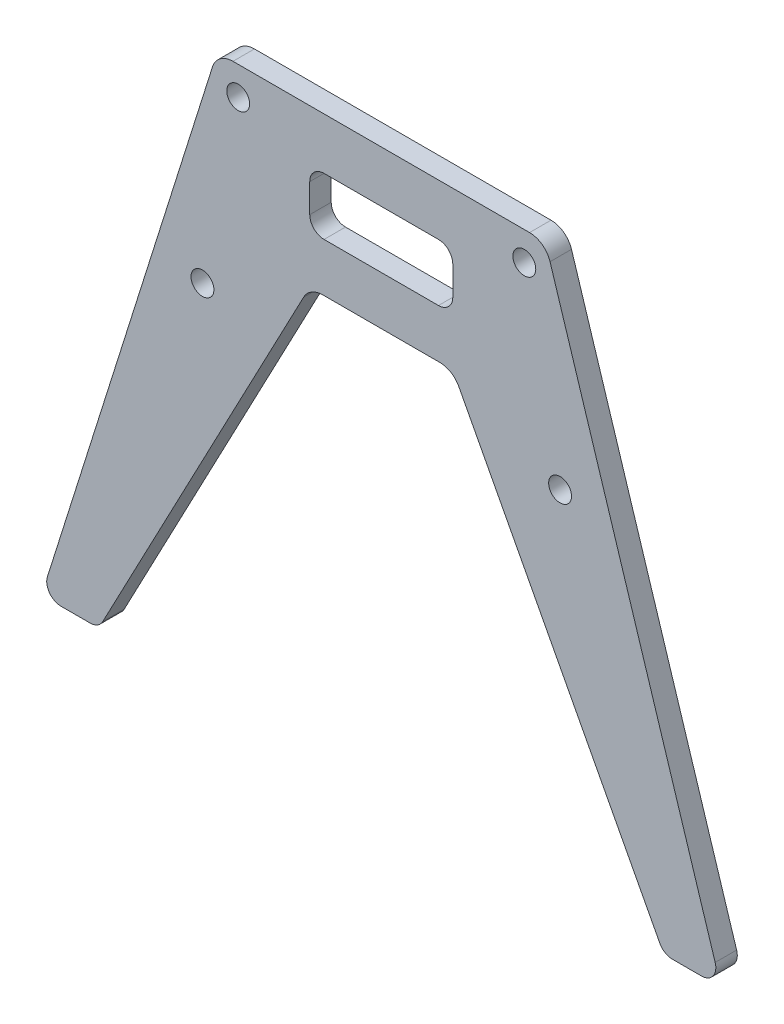
SolidWorks part; units mm, degrees
material "Thornel Mat VMA"
ref_plane "前视基准面" through (0, 0, 0) normal (0, 0, 1) x (1, 0, 0)
ref_plane "上视基准面" through (0, 0, 0) normal (0, 1, 0) x (1, 0, 0)
ref_plane "右视基准面" through (0, 0, 0) normal (1, 0, 0) x (0, 0, -1)
other "Configuration Table"
sketch "草图2" plane through (0, 0, 0) normal (0, 0, 1) x (1, 0, 0)
  line L0 (-20, 14) -> (20, 14) construction
  line L1 (20, 14) -> (42.0465, -56) construction
  line L2 (42.0465, -56) -> (41.9139, -56) construction
  line L3 (41.9139, -56) -> (12.4139, 0) construction
  line L4 (-32, 0) -> (32, 0) construction
  line L5 (12.4139, 0) -> (-12.4139, 0) construction
  line L6 (0, 0) -> (0, -14.6953) construction
  line L7 (-41.9139, -56) -> (-12.4139, 0) construction
  line L8 (-42.0465, -56) -> (-41.9139, -56) construction
  line L9 (-20, 14) -> (-42.0465, -56) construction
  line L10 (-22.9339, 18) -> (-47.5, -60)
  line L11 (-47.5, -60) -> (-39.5, -60)
  line L12 (-39.5, -60) -> (-10, -4)
  line L13 (10, -4) -> (-10, -4)
  line L14 (39.5, -60) -> (10, -4)
  line L15 (47.5, -60) -> (39.5, -60)
  line L16 (22.9339, 18) -> (47.5, -60)
  line L17 (-22.9339, 18) -> (22.9339, 18)
  circle A0 centre (-20, 14) radius 1.6 construction
  circle A1 centre (-20, 14) radius 1.6
  circle A2 centre (20, 14) radius 1.6 construction
  circle A3 centre (20, 14) radius 1.6
  dimension "D1" = 95
  dimension "D2" = 8
  dimension "D3" = 70
  dimension "D4" = 20
  dimension "D5" = 4
extrude "凸台-拉伸1" add sketch "草图2" along normal blind 3
fillet "圆角1" radius 3 2 edges at (22.9339, 18, 1.5) (-22.9339, 18, 1.5)
fillet "圆角2" radius 2 4 edges at (47.5, -60, 1.5) (39.5, -60, 1.5) (-39.5, -60, 1.5) (-47.5, -60, 1.5)
fillet "圆角3" radius 3 2 edges at (10, -4, 1.5) (-10, -4, 1.5)
sketch "草图4" plane through (0, 0, 3) normal (0, 0, 1) x (1, 0, 0)
  line L1 (-10, 10.8) -> (10, 10.8)
  line L2 (-10, 10.8) -> (-10, 2.8)
  line L3 (-10, 2.8) -> (10, 2.8)
  line L4 (10, 10.8) -> (10, 2.8)
  point P4 (0, 2.8)
  dimension "D1" = 8
  dimension "D2" = 20
  dimension "D3" = 2.8
extrude "切除-拉伸2" cut sketch "草图4" against normal through all
fillet "圆角5" radius 2 4 edges at (10, 10.8, 1.5) (10, 2.8, 1.5) (-10, 2.8, 1.5) (-10, 10.8, 1.5)
sketch "草图5" plane through (0, 0, 3) normal (0, 0, 1) x (1, 0, 0)
  line L1 (25, 11) -> (-25, 11) construction
  line L2 (25, 11) -> (25, -11) construction
  line L3 (25, -11) -> (-25, -11) construction
  line L4 (-25, 11) -> (-25, -11) construction
  line L5 (25, 11) -> (-25, -11) construction
  line L6 (25, -11) -> (-25, 11) construction
  circle A0 centre (-25, -11) radius 1.6
  circle A1 centre (25, -11) radius 1.6
  circle A2 centre (-20, 14) radius 1.6 construction
  point P0 (0, 0)
  dimension "D3" = 3.2
  dimension "D2" = 25
  dimension "D1" = 50
extrude "切除-拉伸3" cut sketch "草图5" against normal through all
